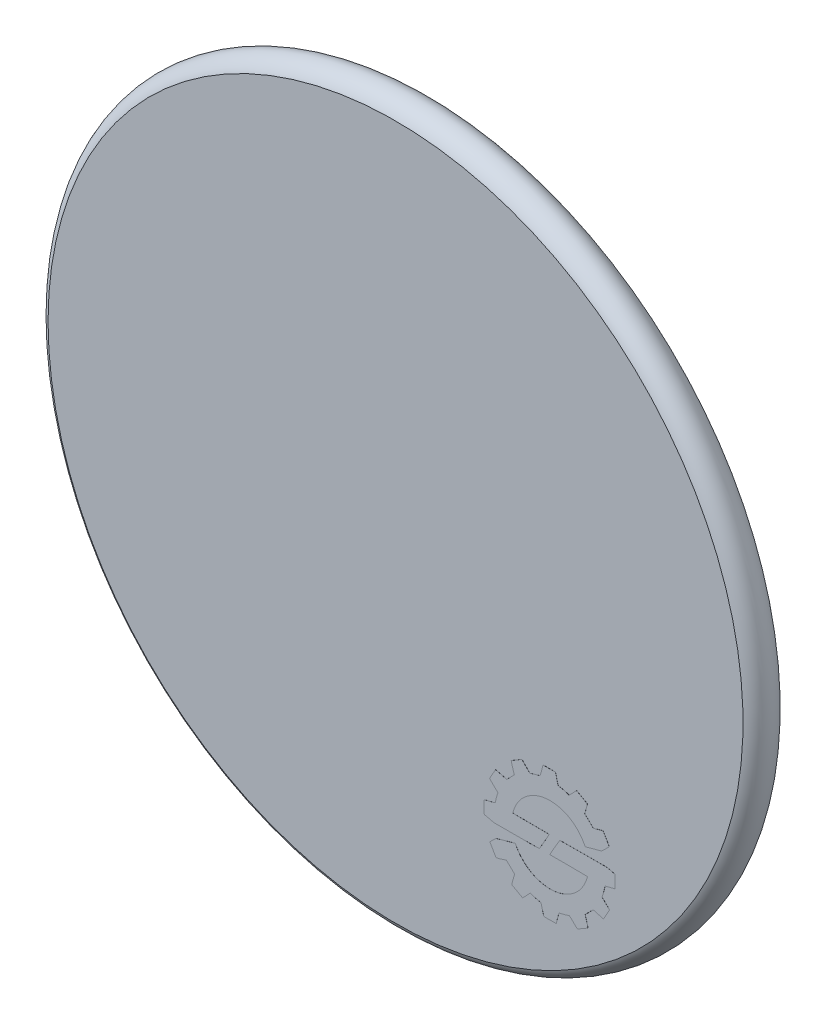
SolidWorks part; units mm, degrees
ref_plane "Front Plane" through (0, 0, 0) normal (0, 0, 1) x (1, 0, 0)
ref_plane "Top Plane" through (0, 0, 0) normal (0, 1, 0) x (1, 0, 0)
ref_plane "Right Plane" through (0, 0, 0) normal (1, 0, 0) x (0, 0, -1)
sketch "Sketch1" plane through (0, 0, 0) normal (0, 1, 0) x (1, 0, 0)
  line L0 (0, 0) -> (-40, 0)
  line L3 (-40, 0) -> (-42, 1.5)
  line L4 (0, 0) -> (0, -3)
  line L5 (0, -3) -> (-42, -3)
  line L6 (-42, -3) -> (-44.5, -3)
  line L8 (-44.5, 1.5) -> (-42, 1.5)
  arc A0 (-44.5, 1.5) -> (-44.5, -3) centre (-43.5625, -0.75) ccw
  dimension "D1" = 40
  dimension "D2" = 42
revolve "Revolve1" add sketch "Sketch1" angle 360 about L4
sketch "Sketch5" plane through (0, 0, 3) normal (0, 0, 1) x (1, 0, 0)
  line L0 (16.6947, -18.7297) -> (16.1934, -18.2222)
  line L1 (16.1934, -18.2222) -> (16.1083, -18.2709)
  line L2 (14.8898, -18.991) -> (14.8169, -19.0457)
  line L3 (14.8169, -19.0457) -> (14.8685, -19.2432)
  line L4 (15.1116, -20.0667) -> (15.221, -20.4222)
  line L5 (15.221, -20.4222) -> (14.8777, -20.7655)
  line L6 (12.1187, -22.2757) -> (12.0518, -22.4124)
  line L7 (12.0518, -22.4124) -> (12.3374, -22.6859)
  line L8 (12.1004, -26.8973) -> (12.617, -27.0189)
  line L9 (12.617, -27.0189) -> (15.4915, -27.0189)
  line L10 (24.1878, -23.6491) -> (24.2911, -23.8497)
  line L11 (24.2911, -23.8497) -> (24.4856, -23.798)
  line L12 (25.543, -23.5093) -> (26.3999, -23.2723)
  line L13 (26.3999, -23.2723) -> (26.886, -22.8014)
  line L14 (26.6186, -21.0056) -> (26.5609, -20.9326)
  line L15 (26.5609, -20.9326) -> (26.2145, -21.0329)
  line L16 (24.4734, -20.4404) -> (24.2364, -20.2277)
  line L17 (24.2364, -20.2277) -> (24.3914, -19.6808)
  line L18 (23.4221, -18.3013) -> (23.1942, -18.1706)
  line L19 (23.1942, -18.1706) -> (22.7202, -18.6659)
  line L20 (22.7202, -18.6659) -> (22.2462, -19.1612)
  line L21 (22.2462, -19.1612) -> (22.0669, -19.0943)
  line L22 (20.5294, -17.5963) -> (20.496, -17.4778)
  line L23 (20.496, -17.4778) -> (19.6938, -17.4778)
  line L24 (20.3805, -25.8885) -> (19.7515, -26.9885)
  line L25 (19.7515, -26.9885) -> (22.1641, -26.9885)
  line L26 (12.4438, -29.0486) -> (12.0822, -29.4102)
  line L27 (12.0822, -29.4102) -> (12.2189, -29.6351)
  line L28 (14.747, -30.8961) -> (15.2544, -31.4035)
  line L29 (15.2544, -31.4035) -> (15.1299, -31.8623)
  line L30 (16.1721, -33.4697) -> (16.2906, -33.5274)
  line L31 (16.2906, -33.5274) -> (16.4608, -33.3482)
  line L32 (16.9408, -32.8438) -> (17.2538, -32.5156)
  line L33 (17.2538, -32.5156) -> (17.5273, -32.6098)
  line L34 (20.3562, -34.2202) -> (20.5871, -34.2202)
  line L35 (20.5871, -34.2202) -> (20.7451, -33.567)
  line L36 (25.2057, -30.4403) -> (25.3029, -30.3218)
  line L37 (25.3029, -30.3218) -> (25.6007, -30.4069)
  line L38 (26.2692, -30.5892) -> (26.6399, -30.6894)
  line L39 (26.6399, -30.6894) -> (26.7888, -30.4281)
  line L40 (26.6916, -28.5928) -> (26.4485, -28.3649)
  line L41 (26.4485, -28.3649) -> (26.5731, -27.9882)
  line L42 (27.5089, -26.7606) -> (28.1166, -26.6087)
  line L43 (28.1166, -26.6087) -> (28.1166, -25.8034)
  line L44 (28.1166, -25.8034) -> (28.1166, -24.9982)
  line L45 (28.1166, -24.9982) -> (27.6153, -24.8706)
  line L46 (27.6153, -24.8706) -> (27.1139, -24.746)
  line L47 (27.1139, -24.746) -> (24.1209, -24.746)
  spline S0 degree 3 poles (18.8916, -17.4839) (18.8916, -17.49) (18.8126, -17.7999) (18.7184, -18.1767) knots 0 0 0 0 1 1 1 1
  spline S1 degree 3 poles (18.7184, -18.1767) (18.5239, -18.9424) (18.5756, -18.8603) (18.2262, -18.9393) knots 0 0 0 0 1 1 1 1
  spline S2 degree 3 poles (18.2262, -18.9393) (18.135, -18.9576) (17.8737, -19.0335) (17.6488, -19.1065) knots 0 0 0 0 1 1 1 1
  spline S3 degree 3 poles (17.6488, -19.1065) (17.424, -19.1794) (17.2295, -19.2402) (17.2174, -19.2402) knots 0 0 0 0 1 1 1 1
  spline S4 degree 3 poles (17.2174, -19.2402) (17.2052, -19.2402) (16.9682, -19.0123) (16.6947, -18.7297) knots 0 0 0 0 1 1 1 1
  spline S5 degree 3 poles (16.1083, -18.2709) (15.3881, -18.6871) (14.9476, -18.9485) (14.8898, -18.991) knots 0 0 0 0 1 1 1 1
  spline S6 degree 3 poles (14.8685, -19.2432) (14.9232, -19.4529) (14.9415, -19.5197) (15.1116, -20.0667) knots 0 0 0 0 1 1 1 1
  spline S7 degree 3 poles (14.8777, -20.7655) (14.6893, -20.9539) (14.4796, -21.1727) (14.4128, -21.2517) knots 0 0 0 0 1 1 1 1
  spline S8 degree 3 poles (14.4128, -21.2517) (14.3459, -21.3307) (14.27, -21.3975) (14.2456, -21.3975) knots 0 0 0 0 1 1 1 1
  spline S9 degree 3 poles (14.2456, -21.3975) (14.2213, -21.3975) (14.0573, -21.355) (13.881, -21.3064) knots 0 0 0 0 1 1 1 1
  spline S10 degree 3 poles (13.881, -21.3064) (13.2399, -21.121) (12.8418, -21.0268) (12.8175, -21.0511) knots 0 0 0 0 1 1 1 1
  spline S11 degree 3 poles (12.8175, -21.0511) (12.8054, -21.0663) (12.7324, -21.1879) (12.6595, -21.3216) knots 0 0 0 0 1 1 1 1
  spline S12 degree 3 poles (12.6595, -21.3216) (12.5836, -21.4553) (12.4468, -21.6953) (12.3557, -21.8533) knots 0 0 0 0 1 1 1 1
  spline S13 degree 3 poles (12.3557, -21.8533) (12.2645, -22.0113) (12.1582, -22.2028) (12.1187, -22.2757) knots 0 0 0 0 1 1 1 1
  spline S14 degree 3 poles (12.3374, -22.6859) (12.4924, -22.8378) (12.7324, -23.0687) (12.8722, -23.2024) knots 0 0 0 0 1 1 1 1
  spline S15 degree 3 poles (12.8722, -23.2024) (13.009, -23.3331) (13.1214, -23.4486) (13.1214, -23.4546) knots 0 0 0 0 1 1 1 1
  spline S16 degree 3 poles (13.1214, -23.4546) (13.1214, -23.4638) (13.0819, -23.5792) (13.0333, -23.716) knots 0 0 0 0 1 1 1 1
  spline S17 degree 3 poles (13.0333, -23.716) (12.9877, -23.8527) (12.9178, -24.1019) (12.8783, -24.269) knots 0 0 0 0 1 1 1 1
  spline S18 degree 3 poles (12.8783, -24.269) (12.8418, -24.4361) (12.8023, -24.6123) (12.7902, -24.6609) knots 0 0 0 0 1 1 1 1
  spline S19 degree 3 poles (12.7902, -24.6609) (12.7689, -24.7491) (12.7568, -24.7551) (12.3162, -24.8645) knots 0 0 0 0 1 1 1 1
  spline S20 degree 3 poles (12.3162, -24.8645) (12.064, -24.9253) (11.7571, -25.0013) (11.6325, -25.0316) knots 0 0 0 0 1 1 1 1
  spline S21 degree 3 poles (11.6325, -25.0316) (11.5079, -25.059) (11.3864, -25.0955) (11.3651, -25.1137) knots 0 0 0 0 1 1 1 1
  spline S22 degree 3 poles (11.3651, -25.1137) (11.3377, -25.135) (11.3286, -25.3234) (11.3317, -25.8916) knots 0 0 0 0 1 1 1 1
  spline S23 degree 3 poles (11.3317, -25.8916) (11.3317, -26.3018) (11.3469, -26.6603) (11.359, -26.6877) knots 0 0 0 0 1 1 1 1
  spline S24 degree 3 poles (11.359, -26.6877) (11.3742, -26.715) (11.4319, -26.7454) (11.4866, -26.7545) knots 0 0 0 0 1 1 1 1
  spline S25 degree 3 poles (11.4866, -26.7545) (11.5413, -26.7636) (11.8178, -26.8274) (12.1004, -26.8973) knots 0 0 0 0 1 1 1 1
  spline S26 degree 3 poles (15.4915, -27.0189) (17.7461, -27.0189) (18.3781, -27.0097) (18.4145, -26.9794) knots 0 0 0 0 1 1 1 1
  spline S27 degree 3 poles (18.4145, -26.9794) (18.4389, -26.9611) (18.5969, -26.7029) (18.764, -26.4112) knots 0 0 0 0 1 1 1 1
  spline S28 degree 3 poles (18.764, -26.4112) (18.9311, -26.1195) (19.2076, -25.6394) (19.3778, -25.3446) knots 0 0 0 0 1 1 1 1
  spline S29 degree 3 poles (19.3778, -25.3446) (19.5449, -25.0499) (19.6847, -24.7977) (19.6847, -24.7886) knots 0 0 0 0 1 1 1 1
  spline S30 degree 3 poles (19.6847, -24.7886) (19.6847, -24.7794) (18.6394, -24.7703) (17.3602, -24.7703) knots 0 0 0 0 1 1 1 1
  spline S31 degree 3 poles (17.3602, -24.7703) (15.139, -24.7703) (15.0357, -24.7673) (15.0357, -24.7156) knots 0 0 0 0 1 1 1 1
  spline S32 degree 3 poles (15.0357, -24.7156) (15.0357, -24.6458) (15.218, -24.1079) (15.3152, -23.8892) knots 0 0 0 0 1 1 1 1
  spline S33 degree 3 poles (15.3152, -23.8892) (16.1295, -22.0691) (18.0074, -20.8992) (19.9733, -20.9843) knots 0 0 0 0 1 1 1 1
  spline S34 degree 3 poles (19.9733, -20.9843) (21.4926, -21.0481) (22.7809, -21.7105) (23.7077, -22.8955) knots 0 0 0 0 1 1 1 1
  spline S35 degree 3 poles (23.7077, -22.8955) (23.8171, -23.0384) (23.9082, -23.1599) (23.9082, -23.169) knots 0 0 0 0 1 1 1 1
  spline S36 degree 3 poles (23.9082, -23.169) (23.9082, -23.1781) (23.9478, -23.245) (23.9964, -23.3179) knots 0 0 0 0 1 1 1 1
  spline S37 degree 3 poles (23.9964, -23.3179) (24.0419, -23.3908) (24.1301, -23.5397) (24.1878, -23.6491) knots 0 0 0 0 1 1 1 1
  spline S38 degree 3 poles (24.4856, -23.798) (24.595, -23.7706) (25.069, -23.64) (25.543, -23.5093) knots 0 0 0 0 1 1 1 1
  spline S39 degree 3 poles (26.886, -22.8014) (27.1534, -22.54) (27.3722, -22.3182) (27.3722, -22.3061) knots 0 0 0 0 1 1 1 1
  spline S40 degree 3 poles (27.3722, -22.3061) (27.3722, -22.2909) (27.2324, -22.0447) (27.0653, -21.7561) knots 0 0 0 0 1 1 1 1
  spline S41 degree 3 poles (27.0653, -21.7561) (26.8951, -21.4674) (26.7371, -21.197) (26.7159, -21.1545) knots 0 0 0 0 1 1 1 1
  spline S42 degree 3 poles (26.7159, -21.1545) (26.6916, -21.1119) (26.649, -21.0451) (26.6186, -21.0056) knots 0 0 0 0 1 1 1 1
  spline S43 degree 3 poles (26.2145, -21.0329) (26.0231, -21.0846) (25.7648, -21.1636) (25.6372, -21.2031) knots 0 0 0 0 1 1 1 1
  spline S44 degree 3 poles (25.6372, -21.2031) (25.5096, -21.2426) (25.385, -21.276) (25.3576, -21.276) knots 0 0 0 0 1 1 1 1
  spline S45 degree 3 poles (25.3576, -21.276) (25.3333, -21.276) (25.2513, -21.2122) (25.1784, -21.1332) knots 0 0 0 0 1 1 1 1
  spline S46 degree 3 poles (25.1784, -21.1332) (24.9596, -20.8962) (24.7256, -20.6652) (24.4734, -20.4404) knots 0 0 0 0 1 1 1 1
  spline S47 degree 3 poles (24.3914, -19.6808) (24.6071, -18.912) (24.6041, -18.9637) (24.4643, -18.8907) knots 0 0 0 0 1 1 1 1
  spline S48 degree 3 poles (24.4643, -18.8907) (24.4005, -18.8573) (24.1908, -18.7388) (23.9994, -18.6294) knots 0 0 0 0 1 1 1 1
  spline S49 degree 3 poles (23.9994, -18.6294) (23.808, -18.52) (23.5467, -18.3711) (23.4221, -18.3013) knots 0 0 0 0 1 1 1 1
  spline S50 degree 3 poles (22.0669, -19.0943) (21.8299, -19.0092) (21.3467, -18.8847) (21.1584, -18.8603) knots 0 0 0 0 1 1 1 1
  spline S51 degree 3 poles (21.1584, -18.8603) (20.815, -18.8148) (20.8363, -18.8421) (20.6935, -18.3043) knots 0 0 0 0 1 1 1 1
  spline S52 degree 3 poles (20.6935, -18.3043) (20.6236, -18.0399) (20.5658, -17.7999) (20.5658, -17.7695) knots 0 0 0 0 1 1 1 1
  spline S53 degree 3 poles (20.5658, -17.7695) (20.5658, -17.7391) (20.5506, -17.6601) (20.5294, -17.5963) knots 0 0 0 0 1 1 1 1
  spline S54 degree 3 poles (19.6938, -17.4778) (19.2562, -17.4778) (18.8946, -17.4808) (18.8916, -17.4839) knots 0 0 0 0 1 1 1 1
  spline S55 degree 3 poles (21.0702, -24.7673) (21.0368, -24.7794) (20.7542, -25.2413) (20.3805, -25.8885) knots 0 0 0 0 1 1 1 1
  spline S56 degree 3 poles (22.1641, -26.9885) (24.1453, -26.9885) (24.5767, -26.9946) (24.5767, -27.028) knots 0 0 0 0 1 1 1 1
  spline S57 degree 3 poles (24.5767, -27.028) (24.5767, -27.0523) (24.5433, -27.1829) (24.5008, -27.3197) knots 0 0 0 0 1 1 1 1
  spline S58 degree 3 poles (24.5008, -27.3197) (24.285, -28.0398) (23.8171, -28.8116) (23.2762, -29.3494) knots 0 0 0 0 1 1 1 1
  spline S59 degree 3 poles (23.2762, -29.3494) (22.5774, -30.0361) (21.8238, -30.4433) (20.8089, -30.6834) knots 0 0 0 0 1 1 1 1
  spline S60 degree 3 poles (20.8089, -30.6834) (20.3228, -30.7958) (19.5631, -30.814) (19.0466, -30.7259) knots 0 0 0 0 1 1 1 1
  spline S61 degree 3 poles (19.0466, -30.7259) (17.6124, -30.4767) (16.5306, -29.787) (15.7011, -28.5837) knots 0 0 0 0 1 1 1 1
  spline S62 degree 3 poles (15.7011, -28.5837) (15.6434, -28.4986) (15.5401, -28.3254) (15.4763, -28.1978) knots 0 0 0 0 1 1 1 1
  spline S63 degree 3 poles (15.4763, -28.1978) (15.4094, -28.0672) (15.3395, -27.9608) (15.3243, -27.9608) knots 0 0 0 0 1 1 1 1
  spline S64 degree 3 poles (15.3243, -27.9608) (15.3061, -27.9608) (15.1754, -27.9942) (15.0357, -28.0337) knots 0 0 0 0 1 1 1 1
  spline S65 degree 3 poles (15.0357, -28.0337) (14.8929, -28.0763) (14.3672, -28.2191) (13.8658, -28.3558) knots 0 0 0 0 1 1 1 1
  spline S66 degree 3 poles (13.8658, -28.3558) (13.3645, -28.4956) (12.9208, -28.6232) (12.8783, -28.6445) knots 0 0 0 0 1 1 1 1
  spline S67 degree 3 poles (12.8783, -28.6445) (12.8358, -28.6688) (12.6413, -28.8481) (12.4438, -29.0486) knots 0 0 0 0 1 1 1 1
  spline S68 degree 3 poles (12.2189, -29.6351) (12.3496, -29.8538) (12.5289, -30.1577) (12.6352, -30.3461) knots 0 0 0 0 1 1 1 1
  spline S69 degree 3 poles (12.6352, -30.3461) (12.6626, -30.3947) (12.7324, -30.5102) (12.7871, -30.6013) knots 0 0 0 0 1 1 1 1
  spline S70 degree 3 poles (12.7871, -30.6013) (12.8844, -30.7593) (12.8904, -30.7624) (13.0029, -30.7441) knots 0 0 0 0 1 1 1 1
  spline S71 degree 3 poles (13.0029, -30.7441) (13.0667, -30.735) (13.2247, -30.6925) (13.3553, -30.653) knots 0 0 0 0 1 1 1 1
  spline S72 degree 3 poles (13.3553, -30.653) (13.486, -30.6104) (13.7261, -30.5375) (13.8901, -30.4859) knots 0 0 0 0 1 1 1 1
  spline S73 degree 3 poles (13.8901, -30.4859) (14.0542, -30.4342) (14.2001, -30.3917) (14.2153, -30.3917) knots 0 0 0 0 1 1 1 1
  spline S74 degree 3 poles (14.2153, -30.3917) (14.2305, -30.3917) (14.4705, -30.6196) (14.747, -30.8961) knots 0 0 0 0 1 1 1 1
  spline S75 degree 3 poles (15.1299, -31.8623) (15.06, -32.1145) (14.9749, -32.4062) (14.9445, -32.5126) knots 0 0 0 0 1 1 1 1
  spline S76 degree 3 poles (14.9445, -32.5126) (14.8898, -32.6949) (14.8898, -32.7921) (14.9476, -32.7921) knots 0 0 0 0 1 1 1 1
  spline S77 degree 3 poles (14.9476, -32.7921) (14.9627, -32.7921) (15.0387, -32.8316) (15.1177, -32.8772) knots 0 0 0 0 1 1 1 1
  spline S78 degree 3 poles (15.1177, -32.8772) (15.3729, -33.0322) (16.0505, -33.4089) (16.1721, -33.4697) knots 0 0 0 0 1 1 1 1
  spline S79 degree 3 poles (16.4608, -33.3482) (16.5549, -33.2509) (16.7707, -33.023) (16.9408, -32.8438) knots 0 0 0 0 1 1 1 1
  spline S80 degree 3 poles (17.5273, -32.6098) (17.7795, -32.6949) (18.2687, -32.8195) (18.5361, -32.865) knots 0 0 0 0 1 1 1 1
  spline S81 degree 3 poles (18.5361, -32.865) (18.6303, -32.8833) (18.6485, -32.8985) (18.6667, -32.9835) knots 0 0 0 0 1 1 1 1
  spline S82 degree 3 poles (18.6667, -32.9835) (18.7123, -33.2145) (18.9676, -34.1777) (18.9919, -34.2081) knots 0 0 0 0 1 1 1 1
  spline S83 degree 3 poles (18.9919, -34.2081) (19.0101, -34.2324) (19.1833, -34.2415) (19.5722, -34.2324) knots 0 0 0 0 1 1 1 1
  spline S84 degree 3 poles (19.5722, -34.2324) (19.8761, -34.2263) (20.2286, -34.2233) (20.3562, -34.2202) knots 0 0 0 0 1 1 1 1
  spline S85 degree 3 poles (20.7451, -33.567) (20.8332, -33.2084) (20.9244, -32.9015) (20.9457, -32.8833) knots 0 0 0 0 1 1 1 1
  spline S86 degree 3 poles (20.9457, -32.8833) (20.9639, -32.8681) (21.055, -32.8377) (21.1462, -32.8225) knots 0 0 0 0 1 1 1 1
  spline S87 degree 3 poles (21.1462, -32.8225) (21.3802, -32.78) (22.0942, -32.5764) (22.1307, -32.546) knots 0 0 0 0 1 1 1 1
  spline S88 degree 3 poles (22.1307, -32.546) (22.1459, -32.5308) (22.1945, -32.5186) (22.2431, -32.5186) knots 0 0 0 0 1 1 1 1
  spline S89 degree 3 poles (22.2431, -32.5186) (22.31, -32.5186) (22.4133, -32.6068) (22.787, -32.9896) knots 0 0 0 0 1 1 1 1
  spline S90 degree 3 poles (22.787, -32.9896) (23.0423, -33.2479) (23.2732, -33.4606) (23.2975, -33.4606) knots 0 0 0 0 1 1 1 1
  spline S91 degree 3 poles (23.2975, -33.4606) (23.3248, -33.4606) (23.3735, -33.4424) (23.4069, -33.4181) knots 0 0 0 0 1 1 1 1
  spline S92 degree 3 poles (23.4069, -33.4181) (23.4403, -33.3968) (23.5163, -33.3512) (23.574, -33.3178) knots 0 0 0 0 1 1 1 1
  spline S93 degree 3 poles (23.574, -33.3178) (23.6895, -33.2509) (23.9721, -33.0869) (24.1361, -32.9896) knots 0 0 0 0 1 1 1 1
  spline S94 degree 3 poles (24.1361, -32.9896) (24.1939, -32.9562) (24.3306, -32.8772) (24.44, -32.8134) knots 0 0 0 0 1 1 1 1
  spline S95 degree 3 poles (24.44, -32.8134) (24.6648, -32.6827) (24.6679, -32.6706) (24.5767, -32.3698) knots 0 0 0 0 1 1 1 1
  spline S96 degree 3 poles (24.5767, -32.3698) (24.3944, -31.762) (24.3033, -31.44) (24.3033, -31.3913) knots 0 0 0 0 1 1 1 1
  spline S97 degree 3 poles (24.3033, -31.3913) (24.3033, -31.364) (24.3549, -31.2941) (24.4187, -31.2364) knots 0 0 0 0 1 1 1 1
  spline S98 degree 3 poles (24.4187, -31.2364) (24.598, -31.0753) (25.0994, -30.5709) (25.2057, -30.4403) knots 0 0 0 0 1 1 1 1
  spline S99 degree 3 poles (25.6007, -30.4069) (25.7648, -30.4524) (26.0656, -30.5345) (26.2692, -30.5892) knots 0 0 0 0 1 1 1 1
  spline S100 degree 3 poles (26.7888, -30.4281) (27.2871, -29.5439) (27.4026, -29.3312) (27.4026, -29.3039) knots 0 0 0 0 1 1 1 1
  spline S101 degree 3 poles (27.4026, -29.3039) (27.4026, -29.2765) (27.2659, -29.1367) (26.6916, -28.5928) knots 0 0 0 0 1 1 1 1
  spline S102 degree 3 poles (26.5731, -27.9882) (26.6429, -27.7815) (26.7311, -27.4595) (26.7675, -27.2771) knots 0 0 0 0 1 1 1 1
  spline S103 degree 3 poles (26.7675, -27.2771) (26.807, -27.0918) (26.8526, -26.9368) (26.8708, -26.9277) knots 0 0 0 0 1 1 1 1
  spline S104 degree 3 poles (26.8708, -26.9277) (26.886, -26.9216) (27.1747, -26.8457) (27.5089, -26.7606) knots 0 0 0 0 1 1 1 1
  spline S105 degree 3 poles (24.1209, -24.746) (22.4741, -24.746) (21.1006, -24.7551) (21.0702, -24.7673) knots 0 0 0 0 1 1 1 1
extrude "Boss-Extrude2" add sketch "Sketch5" along normal blind 0.01
sketch "Sketch7" plane through (0, 0, 0) normal (0, 0, -1) x (-1, 0, 0)
  line L0 (-6.522, -6.0766) -> (-1.7102, -6.0766)
  line L1 (-1.7102, -6.0766) -> (-1.7102, 11.8445)
  line L2 (-1.7102, 11.8445) -> (-1.7102, 29.7656)
  line L3 (-1.7102, 29.7656) -> (-6.5362, 29.7515)
  line L4 (-4.7017, 10.9978) -> (-4.744, -2.9016)
  line L5 (-4.744, -2.9016) -> (-8.0037, -2.9016)
  line L6 (-8.0037, -2.9016) -> (-11.2493, -2.9016)
  line L7 (-11.2493, -2.9016) -> (-12.3076, -2.3795)
  line L8 (-7.6792, 26.647) -> (-4.8428, 26.6612)
  line L9 (-4.8428, 26.6612) -> (-4.744, 25.7863)
  line L10 (16.8883, 12.1973) -> (16.846, 22.4984)
  line L11 (16.846, 22.4984) -> (16.4509, 23.6273)
  line L12 (11.5966, 28.933) -> (10.0726, 29.695)
  line L13 (10.0726, 29.695) -> (5.9522, 29.7374)
  line L14 (5.9522, 29.7374) -> (1.8176, 29.7938)
  line L15 (1.8176, 29.7938) -> (1.7894, 18.3074)
  line L16 (-24.4573, -12.7794) -> (-24.4996, -13.9083)
  line L17 (-24.4996, -13.9083) -> (-25.4168, -12.6665)
  line L18 (-26.9267, -11.4389) -> (-27.5335, -11.4389)
  line L19 (-27.5335, -11.4389) -> (-27.5335, -13.7672)
  line L20 (-27.5335, -13.7672) -> (-27.5335, -16.0955)
  line L21 (-27.5335, -16.0955) -> (-26.9691, -16.0955)
  line L22 (-26.9691, -16.0955) -> (-26.4046, -16.0955)
  line L23 (-26.4046, -16.0955) -> (-26.4046, -14.7127)
  line L24 (-23.8364, -16.0955) -> (-23.3002, -16.0955)
  line L25 (-23.3002, -16.0955) -> (-23.3002, -13.7672)
  line L26 (-15.8213, -13.7954) -> (-15.8213, -16.1097)
  line L27 (-15.8213, -16.1097) -> (-15.2851, -16.0673)
  line L28 (-15.2851, -16.0673) -> (-14.7629, -16.025)
  line L29 (-14.7629, -16.025) -> (-14.6924, -14.755)
  line L30 (-14.6924, -14.755) -> (-14.6218, -13.485)
  line L31 (-14.6218, -13.485) -> (-13.9304, -14.4022)
  line L32 (-12.0536, -16.0955) -> (-11.5879, -16.0955)
  line L33 (-11.5879, -16.0955) -> (-11.6162, -13.7249)
  line L34 (-11.6162, -13.7249) -> (-11.6585, -11.3683)
  line L35 (-11.6585, -11.3683) -> (-12.1524, -11.3683)
  line L36 (-12.1524, -11.3683) -> (-12.6463, -11.3683)
  line L37 (-12.6463, -11.3683) -> (-12.7168, -12.6383)
  line L38 (-12.7168, -12.6383) -> (-12.7874, -13.9083)
  line L39 (-12.7874, -13.9083) -> (-13.6764, -12.7089)
  line L40 (-8.6246, -12.0315) -> (-8.6246, -12.5678)
  line L41 (-8.6246, -12.5678) -> (-7.919, -12.5678)
  line L42 (-7.919, -12.5678) -> (-7.2135, -12.5678)
  line L43 (-7.2135, -12.5678) -> (-7.2135, -14.3317)
  line L44 (-7.2135, -14.3317) -> (-7.2135, -16.0955)
  line L45 (-7.2135, -16.0955) -> (-6.5785, -16.0955)
  line L46 (-6.5785, -16.0955) -> (-5.9435, -16.0955)
  line L47 (-5.9435, -16.0955) -> (-5.9435, -14.3317)
  line L48 (-5.9435, -14.3317) -> (-5.9435, -12.5678)
  line L49 (-5.9435, -12.5678) -> (-5.2379, -12.5678)
  line L50 (-6.5644, -11.2978) -> (-4.5324, -11.2978)
  line L51 (-1.569, -13.7954) -> (-1.569, -16.1097)
  line L52 (-1.569, -16.1097) -> (0.3077, -16.0673)
  line L53 (0.3077, -16.0673) -> (2.1704, -16.025)
  line L54 (2.1704, -16.025) -> (2.1704, -15.5311)
  line L55 (2.1704, -15.5311) -> (2.1704, -15.0372)
  line L56 (2.1704, -15.0372) -> (0.9427, -14.9949)
  line L57 (0.9427, -14.9949) -> (-0.299, -14.9525)
  line L58 (-0.299, -14.9525) -> (-0.299, -14.5433)
  line L59 (-0.299, -14.5433) -> (-0.299, -14.12)
  line L60 (-0.299, -14.12) -> (0.8298, -14.12)
  line L61 (0.8298, -14.12) -> (1.9587, -14.12)
  line L62 (1.9587, -14.12) -> (1.9587, -13.6261)
  line L63 (1.9587, -13.6261) -> (1.9587, -13.1322)
  line L64 (1.9587, -13.1322) -> (1.225, -13.104)
  line L65 (0.9851, -12.4266) -> (2.2551, -12.4266)
  line L66 (2.2551, -12.4266) -> (2.2127, -11.8904)
  line L67 (2.2127, -11.8904) -> (2.1704, -11.3683)
  line L68 (2.1704, -11.3683) -> (0.3924, -11.326)
  line L69 (5.6276, -13.7954) -> (5.6276, -16.0955)
  line L70 (5.6276, -16.0955) -> (6.1921, -16.0955)
  line L71 (6.1921, -16.0955) -> (6.7424, -16.0955)
  line L72 (6.7424, -16.0955) -> (6.7847, -14.7973)
  line L73 (6.7847, -14.7973) -> (6.8271, -13.4991)
  line L74 (6.8271, -13.4991) -> (7.8149, -14.7973)
  line L75 (9.3247, -16.0955) -> (9.8469, -16.0955)
  line L76 (9.8469, -16.0955) -> (9.8892, -13.8237)
  line L77 (9.226, -11.4106) -> (8.7462, -11.4671)
  line L78 (8.7462, -11.4671) -> (8.7039, -12.6948)
  line L79 (8.7039, -12.6948) -> (8.6615, -13.9083)
  line L80 (8.6615, -13.9083) -> (7.829, -12.7794)
  line L81 (13.3887, -13.8095) -> (13.3887, -16.1238)
  line L82 (13.3887, -16.1238) -> (14.7716, -16.0673)
  line L83 (15.2232, -14.8255) -> (14.6587, -14.8255)
  line L84 (14.6587, -14.8255) -> (14.6587, -13.6967)
  line L85 (14.6587, -13.6967) -> (14.6587, -12.5678)
  line L86 (14.6587, -12.5678) -> (15.2232, -12.5678)
  line L87 (-20.1675, -13.7249) -> (-20.1252, -16.025)
  line L88 (-20.1252, -16.025) -> (-19.5184, -16.0673)
  line L89 (-19.5184, -16.0673) -> (-18.9257, -16.1097)
  line L90 (-18.9257, -16.1097) -> (-18.9257, -13.7813)
  line L91 (-18.9257, -13.7813) -> (-18.9257, -11.4389)
  line L92 (-18.9257, -11.4389) -> (-19.5607, -11.4389)
  line L93 (-19.5607, -11.4389) -> (-20.1957, -11.4389)
  line L94 (-20.1957, -11.4389) -> (-20.1675, -13.7249)
  line L95 (15.2232, -25.6205) -> (15.8582, -24.9573)
  line L96 (15.8582, -24.9573) -> (15.1526, -24.3364)
  line L97 (-22.1995, -20.0325) -> (-21.1694, -20.3007)
  line L98 (-21.1694, -20.3007) -> (-21.0283, -19.9338)
  line L99 (-15.6519, -26.7918) -> (-14.5089, -26.7494)
  line L100 (-14.5089, -26.7494) -> (-13.8457, -24.3082)
  line L101 (-12.3358, -24.2518) -> (-11.6303, -26.7494)
  line L102 (-11.6303, -26.7494) -> (-10.5578, -26.7918)
  line L103 (-8.046, -18.0711) -> (-8.9915, -18.0711)
  line L104 (-8.9915, -18.0711) -> (-9.2173, -18.8049)
  line L105 (-11.5315, -20.4277) -> (-12.1947, -18.0711)
  line L106 (-12.1947, -18.0711) -> (-13.0696, -18.0711)
  line L107 (-13.0696, -18.0711) -> (-13.9304, -18.0711)
  line L108 (-13.9304, -18.0711) -> (-14.6924, -20.6393)
  line L109 (-16.9502, -18.6638) -> (-17.1054, -18.0711)
  line L110 (-17.1054, -18.0711) -> (-18.1496, -18.0711)
  line L111 (-5.0968, -22.4455) -> (-5.0968, -26.82)
  line L112 (-5.0968, -26.82) -> (-4.0385, -26.82)
  line L113 (-4.0385, -26.82) -> (-2.9802, -26.82)
  line L114 (-2.9802, -26.82) -> (-2.9802, -22.4455)
  line L115 (-2.9802, -22.4455) -> (-2.9802, -18.0711)
  line L116 (-2.9802, -18.0711) -> (-4.0385, -18.0711)
  line L117 (-4.0385, -18.0711) -> (-5.0968, -18.0711)
  line L118 (-5.0968, -18.0711) -> (-5.0968, -22.4455)
  line L119 (0.8722, -20.1595) -> (1.5354, -20.1878)
  line L120 (1.5354, -20.1878) -> (1.5354, -23.5039)
  line L121 (1.5354, -23.5039) -> (1.5354, -26.8341)
  line L122 (1.5354, -26.8341) -> (2.5655, -26.7918)
  line L123 (2.5655, -26.7918) -> (3.5815, -26.7494)
  line L124 (3.5815, -26.7494) -> (3.6239, -23.4898)
  line L125 (3.6239, -23.4898) -> (3.6521, -20.2301)
  line L126 (3.6521, -20.2301) -> (4.527, -20.1313)
  line L127 (5.8252, -20.0467) -> (6.2626, -20.0467)
  line L128 (6.2626, -20.0467) -> (6.2485, -19.1012)
  line L129 (6.2485, -19.1012) -> (6.2203, -18.1417)
  line L130 (6.2203, -18.1417) -> (2.5373, -18.0993)
  line L131 (17.481, -22.4455) -> (17.481, -26.82)
  line L132 (17.481, -26.82) -> (18.4687, -26.82)
  line L133 (18.4687, -26.82) -> (19.4565, -26.82)
  line L134 (19.4565, -26.82) -> (19.4565, -25.1267)
  line L135 (19.4565, -25.1267) -> (19.4565, -23.4333)
  line L136 (19.4565, -23.4333) -> (21.291, -23.4333)
  line L137 (21.291, -23.4333) -> (23.1254, -23.4333)
  line L138 (23.1254, -23.4333) -> (23.1254, -25.1267)
  line L139 (23.1254, -25.1267) -> (23.1254, -26.8341)
  line L140 (23.1254, -26.8341) -> (24.1555, -26.7918)
  line L141 (24.1555, -26.7918) -> (25.1715, -26.7494)
  line L142 (25.1715, -26.7494) -> (25.1715, -22.4455)
  line L143 (25.1715, -22.4455) -> (25.1715, -18.1417)
  line L144 (25.1715, -18.1417) -> (24.1555, -18.0993)
  line L145 (24.1555, -18.0993) -> (23.1254, -18.057)
  line L146 (23.1254, -18.057) -> (23.1254, -19.6939)
  line L147 (23.1254, -19.6939) -> (23.1254, -21.3167)
  line L148 (23.1254, -21.3167) -> (21.291, -21.3167)
  line L149 (21.291, -21.3167) -> (19.4565, -21.3167)
  line L150 (19.4565, -21.3167) -> (19.4565, -19.6939)
  line L151 (19.4565, -19.6939) -> (19.4565, -18.0711)
  line L152 (19.4565, -18.0711) -> (18.4687, -18.0711)
  line L153 (18.4687, -18.0711) -> (17.481, -18.0711)
  line L154 (17.481, -18.0711) -> (17.481, -22.4455)
  line L155 (-4.5324, -11.2978) -> (-4.5324, -12.1585)
  spline S0 degree 3 poles (-11.9407, 29.6104) (-14.5513, 29.0177) (-16.9502, 27.1127) (-18.0932, 24.7279) knots 0 0 0 0 1 1 1 1
  spline S1 degree 3 poles (-18.0932, 24.7279) (-19.0809, 22.6536) (-19.0668, 22.9217) (-19.0668, 11.9574) knots 0 0 0 0 1 1 1 1
  spline S2 degree 3 poles (-19.0668, 11.9574) (-19.0668, 5.4521) (-19.0104, 1.8679) (-18.9116, 1.374) knots 0 0 0 0 1 1 1 1
  spline S3 degree 3 poles (-18.9116, 1.374) (-18.5165, -0.5874) (-17.7122, -2.0832) (-16.3011, -3.4943) knots 0 0 0 0 1 1 1 1
  spline S4 degree 3 poles (-16.3011, -3.4943) (-15.4967, -4.2986) (-15.0311, -4.6232) (-13.9727, -5.1312) knots 0 0 0 0 1 1 1 1
  spline S5 degree 3 poles (-13.9727, -5.1312) (-13.2389, -5.484) (-12.3499, -5.8368) (-11.983, -5.9214) knots 0 0 0 0 1 1 1 1
  spline S6 degree 3 poles (-11.983, -5.9214) (-11.5738, -6.0202) (-9.5418, -6.0766) (-6.522, -6.0766) knots 0 0 0 0 1 1 1 1
  spline S7 degree 3 poles (-6.5362, 29.7515) (-9.2032, 29.7374) (-11.6303, 29.6809) (-11.9407, 29.6104) knots 0 0 0 0 1 1 1 1
  spline S8 degree 3 poles (-4.744, 25.7863) (-4.7017, 25.2924) (-4.6735, 18.646) (-4.7017, 10.9978) knots 0 0 0 0 1 1 1 1
  spline S9 degree 3 poles (-12.3076, -2.3795) (-13.4929, -1.7869) (-14.6077, -0.7709) (-15.1581, 0.2451) knots 0 0 0 0 1 1 1 1
  spline S10 degree 3 poles (-15.1581, 0.2451) (-15.9624, 1.7127) (-15.9624, 1.7832) (-15.9624, 11.7739) knots 0 0 0 0 1 1 1 1
  spline S11 degree 3 poles (-15.9624, 11.7739) (-15.9624, 21.6799) (-15.9483, 21.9198) (-15.2004, 23.4015) knots 0 0 0 0 1 1 1 1
  spline S12 degree 3 poles (-15.2004, 23.4015) (-14.4807, 24.7985) (-12.6463, 26.2096) (-11.1223, 26.52) knots 0 0 0 0 1 1 1 1
  spline S13 degree 3 poles (-11.1223, 26.52) (-10.7977, 26.5765) (-9.2455, 26.6329) (-7.6792, 26.647) knots 0 0 0 0 1 1 1 1
  spline S14 degree 3 poles (-10.7836, 22.4137) (-11.5597, 22.2303) (-12.0113, 21.9621) (-12.5898, 21.3413) knots 0 0 0 0 1 1 1 1
  spline S15 degree 3 poles (-12.5898, 21.3413) (-13.1119, 20.7909) (-13.5635, 19.7185) (-13.5635, 19.027) knots 0 0 0 0 1 1 1 1
  spline S16 degree 3 poles (-13.5635, 19.027) (-13.5635, 18.4061) (-13.126, 17.2631) (-12.6886, 16.7128) knots 0 0 0 0 1 1 1 1
  spline S17 degree 3 poles (-12.6886, 16.7128) (-12.0113, 15.9085) (-11.2775, 15.5839) (-10.0357, 15.5839) knots 0 0 0 0 1 1 1 1
  spline S18 degree 3 poles (-10.0357, 15.5839) (-8.4976, 15.5839) (-7.5522, 16.1625) (-6.8325, 17.5454) knots 0 0 0 0 1 1 1 1
  spline S19 degree 3 poles (-6.8325, 17.5454) (-6.5079, 18.1521) (-6.522, 19.789) (-6.8466, 20.4805) knots 0 0 0 0 1 1 1 1
  spline S20 degree 3 poles (-6.8466, 20.4805) (-7.538, 21.9339) (-9.2737, 22.7947) (-10.7836, 22.4137) knots 0 0 0 0 1 1 1 1
  spline S21 degree 3 poles (1.7894, 18.3074) (1.733, 2.009) (1.7612, -5.9214) (1.86, -6.0343) knots 0 0 0 0 1 1 1 1
  spline S22 degree 3 poles (1.86, -6.0343) (1.9164, -6.0766) (3.5956, -6.119) (5.5853, -6.1049) knots 0 0 0 0 1 1 1 1
  spline S23 degree 3 poles (5.5853, -6.1049) (9.0707, -6.0908) (9.2683, -6.0766) (10.3549, -5.738) knots 0 0 0 0 1 1 1 1
  spline S24 degree 3 poles (10.3549, -5.738) (13.5157, -4.7361) (15.957, -2.1679) (16.6907, 0.9084) knots 0 0 0 0 1 1 1 1
  spline S25 degree 3 poles (16.6907, 0.9084) (16.9024, 1.7974) (16.9165, 2.9827) (16.8883, 12.1973) knots 0 0 0 0 1 1 1 1
  spline S26 degree 3 poles (16.4509, 23.6273) (15.6183, 25.9979) (14.052, 27.7195) (11.5966, 28.933) knots 0 0 0 0 1 1 1 1
  spline S27 degree 3 poles (9.9174, 13.3403) (11.6813, 12.804) (12.7396, 10.9555) (12.274, 9.2057) knots 0 0 0 0 1 1 1 1
  spline S28 degree 3 poles (12.274, 9.2057) (12.0482, 8.4014) (11.3144, 7.47) (10.5665, 7.0467) knots 0 0 0 0 1 1 1 1
  spline S29 degree 3 poles (10.5665, 7.0467) (9.6352, 6.5246) (8.21, 6.5387) (7.3069, 7.0749) knots 0 0 0 0 1 1 1 1
  spline S30 degree 3 poles (7.3069, 7.0749) (5.8393, 7.9357) (5.162, 9.629) (5.6841, 11.1107) knots 0 0 0 0 1 1 1 1
  spline S31 degree 3 poles (5.6841, 11.1107) (6.0792, 12.2114) (6.7989, 12.9169) (8.0124, 13.3403) knots 0 0 0 0 1 1 1 1
  spline S32 degree 3 poles (8.0124, 13.3403) (8.6756, 13.5801) (9.1131, 13.5801) (9.9174, 13.3403) knots 0 0 0 0 1 1 1 1
  spline S33 degree 3 poles (22.0812, -11.3683) (20.9946, -11.7493) (20.4443, -12.6101) (20.4443, -13.9224) knots 0 0 0 0 1 1 1 1
  spline S34 degree 3 poles (20.4443, -13.9224) (20.4443, -14.6139) (20.8676, -15.3053) (21.5591, -15.771) knots 0 0 0 0 1 1 1 1
  spline S35 degree 3 poles (21.5591, -15.771) (21.9401, -16.025) (22.2364, -16.0955) (22.9702, -16.0955) knots 0 0 0 0 1 1 1 1
  spline S36 degree 3 poles (22.9702, -16.0955) (24.0709, -16.0955) (24.7764, -15.7145) (25.1574, -14.9243) knots 0 0 0 0 1 1 1 1
  spline S37 degree 3 poles (25.1574, -14.9243) (25.4396, -14.3175) (25.4538, -13.104) (25.1856, -12.596) knots 0 0 0 0 1 1 1 1
  spline S38 degree 3 poles (25.1856, -12.596) (24.8611, -11.9892) (24.1838, -11.4248) (23.6052, -11.2836) knots 0 0 0 0 1 1 1 1
  spline S39 degree 3 poles (23.6052, -11.2836) (22.8855, -11.1284) (22.7303, -11.1284) (22.0812, -11.3683) knots 0 0 0 0 1 1 1 1
  spline S40 degree 3 poles (23.8028, -12.8923) (24.2825, -13.3439) (24.2261, -14.1341) (23.6758, -14.5998) knots 0 0 0 0 1 1 1 1
  spline S41 degree 3 poles (23.6758, -14.5998) (23.1536, -15.0372) (22.8009, -15.0654) (22.2788, -14.6844) knots 0 0 0 0 1 1 1 1
  spline S42 degree 3 poles (22.2788, -14.6844) (21.4885, -14.12) (21.6155, -13.0052) (22.4904, -12.6242) knots 0 0 0 0 1 1 1 1
  spline S43 degree 3 poles (22.4904, -12.6242) (22.9843, -12.4125) (23.3512, -12.4831) (23.8028, -12.8923) knots 0 0 0 0 1 1 1 1
  spline S44 degree 3 poles (-24.3585, -11.4812) (-24.4008, -11.58) (-24.4432, -12.1585) (-24.4573, -12.7794) knots 0 0 0 0 1 1 1 1
  spline S45 degree 3 poles (-25.4168, -12.6665) (-26.3199, -11.453) (-26.3482, -11.4389) (-26.9267, -11.4389) knots 0 0 0 0 1 1 1 1
  spline S46 degree 3 poles (-26.4046, -14.7127) (-26.4046, -13.358) (-26.4046, -13.3439) (-26.1506, -13.7108) knots 0 0 0 0 1 1 1 1
  spline S47 degree 3 poles (-26.1506, -13.7108) (-26.0236, -13.9224) (-25.5721, -14.5433) (-25.1487, -15.0937) knots 0 0 0 0 1 1 1 1
  spline S48 degree 3 poles (-25.1487, -15.0937) (-24.4291, -16.025) (-24.3444, -16.0955) (-23.8364, -16.0955) knots 0 0 0 0 1 1 1 1
  spline S49 degree 3 poles (-23.3002, -13.7672) (-23.3002, -11.6505) (-23.3284, -11.4389) (-23.5401, -11.4248) knots 0 0 0 0 1 1 1 1
  spline S50 degree 3 poles (-23.5401, -11.4248) (-23.6812, -11.4248) (-23.9069, -11.3965) (-24.0481, -11.3683) knots 0 0 0 0 1 1 1 1
  spline S51 degree 3 poles (-24.0481, -11.3683) (-24.1892, -11.3401) (-24.3303, -11.3965) (-24.3585, -11.4812) knots 0 0 0 0 1 1 1 1
  spline S52 degree 3 poles (-15.7507, -11.4106) (-15.7931, -11.453) (-15.8213, -12.5254) (-15.8213, -13.7954) knots 0 0 0 0 1 1 1 1
  spline S53 degree 3 poles (-13.9304, -14.4022) (-12.8015, -15.898) (-12.5757, -16.0955) (-12.0536, -16.0955) knots 0 0 0 0 1 1 1 1
  spline S54 degree 3 poles (-13.6764, -12.7089) (-14.4807, -11.6223) (-14.6077, -11.4953) (-15.1157, -11.4248) knots 0 0 0 0 1 1 1 1
  spline S55 degree 3 poles (-15.1157, -11.4248) (-15.4262, -11.3824) (-15.7084, -11.3824) (-15.7507, -11.4106) knots 0 0 0 0 1 1 1 1
  spline S56 degree 3 poles (-8.5258, -11.3965) (-8.5823, -11.4389) (-8.6246, -11.7352) (-8.6246, -12.0315) knots 0 0 0 0 1 1 1 1
  spline S57 degree 3 poles (-5.2379, -12.5678) (-4.5465, -12.5678) (-4.5324, -12.5536) (-4.5324, -12.1585) knots 0 0 0 0 1 1 1 1
  spline S58 degree 3 poles (-6.5644, -11.2978) (-7.5945, -11.2978) (-8.4835, -11.3401) (-8.5258, -11.3965) knots 0 0 0 0 1 1 1 1
  spline S59 degree 3 poles (-1.4703, -11.3824) (-1.5267, -11.4389) (-1.569, -12.5254) (-1.569, -13.7954) knots 0 0 0 0 1 1 1 1
  spline S60 degree 3 poles (1.225, -13.104) (0.8157, -13.0899) (0.3783, -13.0758) (0.2654, -13.0475) knots 0 0 0 0 1 1 1 1
  spline S61 degree 3 poles (0.2654, -13.0475) (0.1525, -13.0334) (-0.0309, -13.0193) (-0.1156, -13.0052) knots 0 0 0 0 1 1 1 1
  spline S62 degree 3 poles (-0.1156, -13.0052) (-0.2144, -12.9911) (-0.299, -12.8641) (-0.299, -12.7089) knots 0 0 0 0 1 1 1 1
  spline S63 degree 3 poles (-0.299, -12.7089) (-0.299, -12.4408) (-0.2003, -12.4266) (0.9851, -12.4266) knots 0 0 0 0 1 1 1 1
  spline S64 degree 3 poles (0.3924, -11.326) (-0.5813, -11.3119) (-1.4138, -11.3401) (-1.4703, -11.3824) knots 0 0 0 0 1 1 1 1
  spline S65 degree 3 poles (5.7264, -11.3824) (5.67, -11.4389) (5.6276, -12.5254) (5.6276, -13.7954) knots 0 0 0 0 1 1 1 1
  spline S66 degree 3 poles (7.8149, -14.7973) (8.7462, -16.025) (8.8309, -16.0955) (9.3247, -16.0955) knots 0 0 0 0 1 1 1 1
  spline S67 degree 3 poles (9.8892, -13.8237) (9.9174, -12.5819) (9.8892, -11.5235) (9.8327, -11.453) knots 0 0 0 0 1 1 1 1
  spline S68 degree 3 poles (9.8327, -11.453) (9.7622, -11.3965) (9.4941, -11.3824) (9.226, -11.4106) knots 0 0 0 0 1 1 1 1
  spline S69 degree 3 poles (7.829, -12.7794) (7.3774, -12.1585) (6.9682, -11.6082) (6.9117, -11.5518) knots 0 0 0 0 1 1 1 1
  spline S70 degree 3 poles (6.9117, -11.5518) (6.7706, -11.4106) (5.8393, -11.2695) (5.7264, -11.3824) knots 0 0 0 0 1 1 1 1
  spline S71 degree 3 poles (13.5016, -11.3824) (13.4311, -11.4389) (13.3887, -12.5254) (13.3887, -13.8095) knots 0 0 0 0 1 1 1 1
  spline S72 degree 3 poles (14.7716, -16.0673) (15.8864, -16.025) (16.2392, -15.9544) (16.6625, -15.7004) knots 0 0 0 0 1 1 1 1
  spline S73 degree 3 poles (16.6625, -15.7004) (17.354, -15.2771) (17.6362, -14.7973) (17.7209, -13.9083) knots 0 0 0 0 1 1 1 1
  spline S74 degree 3 poles (17.7209, -13.9083) (17.7914, -13.3015) (17.735, -13.0617) (17.4669, -12.5819) knots 0 0 0 0 1 1 1 1
  spline S75 degree 3 poles (17.4669, -12.5819) (16.973, -11.6929) (16.5073, -11.4671) (14.941, -11.3683) knots 0 0 0 0 1 1 1 1
  spline S76 degree 3 poles (14.941, -11.3683) (14.2072, -11.3119) (13.5581, -11.326) (13.5016, -11.3824) knots 0 0 0 0 1 1 1 1
  spline S77 degree 3 poles (16.1404, -12.9205) (16.9024, -13.6684) (16.3521, -14.8255) (15.2232, -14.8255) knots 0 0 0 0 1 1 1 1
  spline S78 degree 3 poles (15.2232, -12.5678) (15.6465, -12.5678) (15.8864, -12.6665) (16.1404, -12.9205) knots 0 0 0 0 1 1 1 1
  spline S79 degree 3 poles (10.6089, -18.0005) (8.5345, -18.6355) (7.321, -20.3007) (7.321, -22.4738) knots 0 0 0 0 1 1 1 1
  spline S80 degree 3 poles (7.321, -22.4738) (7.3351, -24.2094) (8.1535, -25.5923) (9.7199, -26.5095) knots 0 0 0 0 1 1 1 1
  spline S81 degree 3 poles (9.7199, -26.5095) (10.2984, -26.8623) (10.4819, -26.8905) (11.9071, -26.8905) knots 0 0 0 0 1 1 1 1
  spline S82 degree 3 poles (11.9071, -26.8905) (13.7133, -26.8905) (14.1649, -26.7212) (15.2232, -25.6205) knots 0 0 0 0 1 1 1 1
  spline S83 degree 3 poles (15.1526, -24.3364) (14.7716, -23.9978) (14.3624, -23.7155) (14.2495, -23.7155) knots 0 0 0 0 1 1 1 1
  spline S84 degree 3 poles (14.2495, -23.7155) (14.1507, -23.7155) (13.9391, -23.8708) (13.798, -24.0542) knots 0 0 0 0 1 1 1 1
  spline S85 degree 3 poles (13.798, -24.0542) (13.0077, -25.0702) (11.0745, -25.0984) (10.1573, -24.1248) knots 0 0 0 0 1 1 1 1
  spline S86 degree 3 poles (10.1573, -24.1248) (8.8026, -22.6854) (9.5082, -20.4841) (11.4555, -20.0608) knots 0 0 0 0 1 1 1 1
  spline S87 degree 3 poles (11.4555, -20.0608) (11.8506, -19.962) (12.2457, -19.962) (12.5421, -20.0467) knots 0 0 0 0 1 1 1 1
  spline S88 degree 3 poles (12.5421, -20.0467) (13.1206, -20.216) (13.9532, -20.8369) (13.9532, -21.1191) knots 0 0 0 0 1 1 1 1
  spline S89 degree 3 poles (13.9532, -21.1191) (13.9532, -21.2179) (14.0096, -21.3167) (14.0802, -21.3167) knots 0 0 0 0 1 1 1 1
  spline S90 degree 3 poles (14.0802, -21.3167) (14.2495, -21.3167) (15.7876, -20.0608) (15.7876, -19.9197) knots 0 0 0 0 1 1 1 1
  spline S91 degree 3 poles (15.7876, -19.9197) (15.7876, -19.7362) (14.6023, -18.6214) (14.179, -18.3957) knots 0 0 0 0 1 1 1 1
  spline S92 degree 3 poles (14.179, -18.3957) (13.036, -17.803) (11.6954, -17.6478) (10.6089, -18.0005) knots 0 0 0 0 1 1 1 1
  spline S93 degree 3 poles (-25.1064, -18.0711) (-26.0377, -18.2687) (-26.9691, -18.7908) (-27.4347, -19.3693) knots 0 0 0 0 1 1 1 1
  spline S94 degree 3 poles (-27.4347, -19.3693) (-27.7734, -19.7927) (-27.8439, -20.0184) (-27.8439, -20.597) knots 0 0 0 0 1 1 1 1
  spline S95 degree 3 poles (-27.8439, -20.597) (-27.8439, -22.0787) (-27.0819, -22.629) (-24.1751, -23.2358) knots 0 0 0 0 1 1 1 1
  spline S96 degree 3 poles (-24.1751, -23.2358) (-21.8608, -23.7155) (-21.4657, -24.0401) (-22.3265, -24.7598) knots 0 0 0 0 1 1 1 1
  spline S97 degree 3 poles (-22.3265, -24.7598) (-22.7216, -25.0843) (-22.8768, -25.1267) (-23.9493, -25.1267) knots 0 0 0 0 1 1 1 1
  spline S98 degree 3 poles (-23.9493, -25.1267) (-24.8101, -25.1267) (-25.3745, -25.042) (-25.9531, -24.8303) knots 0 0 0 0 1 1 1 1
  spline S99 degree 3 poles (-25.9531, -24.8303) (-26.3905, -24.6751) (-26.8421, -24.534) (-26.9549, -24.5199) knots 0 0 0 0 1 1 1 1
  spline S100 degree 3 poles (-26.9549, -24.5199) (-27.1948, -24.4917) (-27.9709, -25.8604) (-27.8439, -26.0721) knots 0 0 0 0 1 1 1 1
  spline S101 degree 3 poles (-27.8439, -26.0721) (-27.6323, -26.4108) (-25.8966, -26.8482) (-24.4291, -26.9188) knots 0 0 0 0 1 1 1 1
  spline S102 degree 3 poles (-24.4291, -26.9188) (-21.5081, -27.074) (-19.9135, -26.1285) (-19.9135, -24.2377) knots 0 0 0 0 1 1 1 1
  spline S103 degree 3 poles (-19.9135, -24.2377) (-19.9135, -23.4615) (-20.1675, -22.8265) (-20.6191, -22.4879) knots 0 0 0 0 1 1 1 1
  spline S104 degree 3 poles (-20.6191, -22.4879) (-21.1271, -22.1069) (-22.3829, -21.6553) (-23.4413, -21.4578) knots 0 0 0 0 1 1 1 1
  spline S105 degree 3 poles (-23.4413, -21.4578) (-24.7113, -21.2461) (-25.6567, -20.9215) (-25.7555, -20.6817) knots 0 0 0 0 1 1 1 1
  spline S106 degree 3 poles (-25.7555, -20.6817) (-25.8402, -20.4418) (-25.5015, -20.0749) (-25.0358, -19.8914) knots 0 0 0 0 1 1 1 1
  spline S107 degree 3 poles (-25.0358, -19.8914) (-24.4855, -19.6939) (-23.3143, -19.7503) (-22.1995, -20.0325) knots 0 0 0 0 1 1 1 1
  spline S108 degree 3 poles (-21.0283, -19.9338) (-20.9577, -19.7221) (-20.8166, -19.3693) (-20.7319, -19.1577) knots 0 0 0 0 1 1 1 1
  spline S109 degree 3 poles (-20.7319, -19.1577) (-20.6473, -18.9178) (-20.6332, -18.7061) (-20.7037, -18.6355) knots 0 0 0 0 1 1 1 1
  spline S110 degree 3 poles (-20.7037, -18.6355) (-21.1271, -18.2122) (-24.0339, -17.8453) (-25.1064, -18.0711) knots 0 0 0 0 1 1 1 1
  spline S111 degree 3 poles (-19.2079, -18.184) (-19.2079, -18.2404) (-18.9822, -19.0871) (-18.6999, -20.0467) knots 0 0 0 0 1 1 1 1
  spline S112 degree 3 poles (-18.6999, -20.0467) (-18.4177, -21.0203) (-18.1355, -22.0363) (-18.0508, -22.3044) knots 0 0 0 0 1 1 1 1
  spline S113 degree 3 poles (-18.0508, -22.3044) (-17.7968, -23.2217) (-16.9361, -26.3261) (-16.8655, -26.5801) knots 0 0 0 0 1 1 1 1
  spline S114 degree 3 poles (-16.8655, -26.5801) (-16.7949, -26.7918) (-16.6397, -26.82) (-15.6519, -26.7918) knots 0 0 0 0 1 1 1 1
  spline S115 degree 3 poles (-13.8457, -24.3082) (-13.4647, -22.9535) (-13.1402, -21.8388) (-13.1119, -21.7964) knots 0 0 0 0 1 1 1 1
  spline S116 degree 3 poles (-13.1119, -21.7964) (-13.0696, -21.7682) (-12.7309, -22.8689) (-12.3358, -24.2518) knots 0 0 0 0 1 1 1 1
  spline S117 degree 3 poles (-10.5578, -26.7918) (-9.2596, -26.8341) (-9.4572, -27.1163) (-8.5399, -23.9272) knots 0 0 0 0 1 1 1 1
  spline S118 degree 3 poles (-8.5399, -23.9272) (-7.2276, -19.3693) (-6.9454, -18.2969) (-7.0159, -18.184) knots 0 0 0 0 1 1 1 1
  spline S119 degree 3 poles (-7.0159, -18.184) (-7.0583, -18.1275) (-7.5239, -18.0711) (-8.046, -18.0711) knots 0 0 0 0 1 1 1 1
  spline S120 degree 3 poles (-9.2173, -18.8049) (-9.3443, -19.2141) (-9.6829, -20.47) (-9.9793, -21.5989) knots 0 0 0 0 1 1 1 1
  spline S121 degree 3 poles (-9.9793, -21.5989) (-10.6143, -23.9978) (-10.5014, -24.0824) (-11.5315, -20.4277) knots 0 0 0 0 1 1 1 1
  spline S122 degree 3 poles (-14.6924, -20.6393) (-15.1016, -22.0645) (-15.4826, -23.3063) (-15.5391, -23.4051) knots 0 0 0 0 1 1 1 1
  spline S123 degree 3 poles (-15.5391, -23.4051) (-15.5955, -23.5321) (-15.6943, -23.3628) (-15.7931, -22.9818) knots 0 0 0 0 1 1 1 1
  spline S124 degree 3 poles (-15.7931, -22.9818) (-15.8918, -22.6572) (-16.1458, -21.6694) (-16.3716, -20.8228) knots 0 0 0 0 1 1 1 1
  spline S125 degree 3 poles (-16.3716, -20.8228) (-16.5974, -19.962) (-16.8655, -19.0024) (-16.9502, -18.6638) knots 0 0 0 0 1 1 1 1
  spline S126 degree 3 poles (-18.1496, -18.0711) (-18.7282, -18.0711) (-19.2079, -18.1275) (-19.2079, -18.184) knots 0 0 0 0 1 1 1 1
  spline S127 degree 3 poles (-1.1598, -18.0993) (-1.1739, -18.1275) (-1.188, -18.565) (-1.2022, -19.0871) knots 0 0 0 0 1 1 1 1
  spline S128 degree 3 poles (-1.2022, -19.0871) (-1.2304, -19.6939) (-1.188, -20.0467) (-1.0893, -20.0608) knots 0 0 0 0 1 1 1 1
  spline S129 degree 3 poles (-1.0893, -20.0608) (-0.8494, -20.0749) (0.1243, -20.1172) (0.8722, -20.1595) knots 0 0 0 0 1 1 1 1
  spline S130 degree 3 poles (4.527, -20.1313) (4.9926, -20.089) (5.5853, -20.0467) (5.8252, -20.0467) knots 0 0 0 0 1 1 1 1
  spline S131 degree 3 poles (2.5373, -18.0993) (0.5194, -18.0852) (-1.1598, -18.0852) (-1.1598, -18.0993) knots 0 0 0 0 1 1 1 1
extrude "Boss-Extrude3" add sketch "Sketch7" along normal blind 0.01 contours L3 S7 S0 S1 S2 S3 S4 S5 S6 L0 L1 L2 S12 S13 L8 L9 S8 L4 L5 L6 L7 S9 S10 S11 | L11 S26 L12 L13 L14 L15 S21 S22 S23 S24 S25 L10 S31 S32 S27 S28 S29 S30 | S19 S20 S14 S15 S16 S17 S18 | S50 S51 S44 L16 L17 S45 L18 L19 L20 L21 L22 L23 S46 S47 S48 L24 L25 S49 | S109 S110 S93 S94 S95 S96 S97 S98 S99 S100 S101 S102 S103 S104 S105 S106 S107 L97 L98 S108 | L110 S126 S111 S112 S113 S114 L99 L100 S115 S116 L101 L102 S117 S118 S119 L103 L104 S120 S121 L105 L106 L107 L108 S122 S123 S124 S125 L109 | S54 S55 S52 L26 L27 L28 L29 L30 L31 S53 L32 L33 L34 L35 L36 L37 L38 L39 | L50 S58 S56 L40 L41 L42 L43 L44 L45 L46 L47 L48 L49 S57 L155 | L117 L118 L111 L112 L113 L114 L115 L116 | L130 S131 S127 S128 S129 L119 L120 L121 L122 L123 L124 L125 L126 S130 L127 L128 L129 | L68 S64 S59 L51 L52 L53 L54 L55 L56 L57 L58 L59 L60 L61 L62 L63 L64 S60 S61 S62 S63 L65 L66 L67 | S69 S70 S65 L69 L70 L71 L72 L73 L74 S66 L75 L76 S67 S68 L77 L78 L79 L80 | S91 S92 S79 S80 S81 S82 L95 L96 S83 S84 S85 S86 S87 S88 S89 S90 | S75 S76 S71 L81 L82 S72 S73 S74 L86 S78 S77 L83 L84 L85 | L153 L154 L131 L132 L133 L134 L135 L136 L137 L138 L139 L140 L141 L142 L143 L144 L145 L146 L147 L148 L149 L150 L151 L152 | S38 S39 S33 S34 S35 S36 S37 S42 S43 S40 S41 | L90 L91 L92 L93 L94 L87 L88 L89
